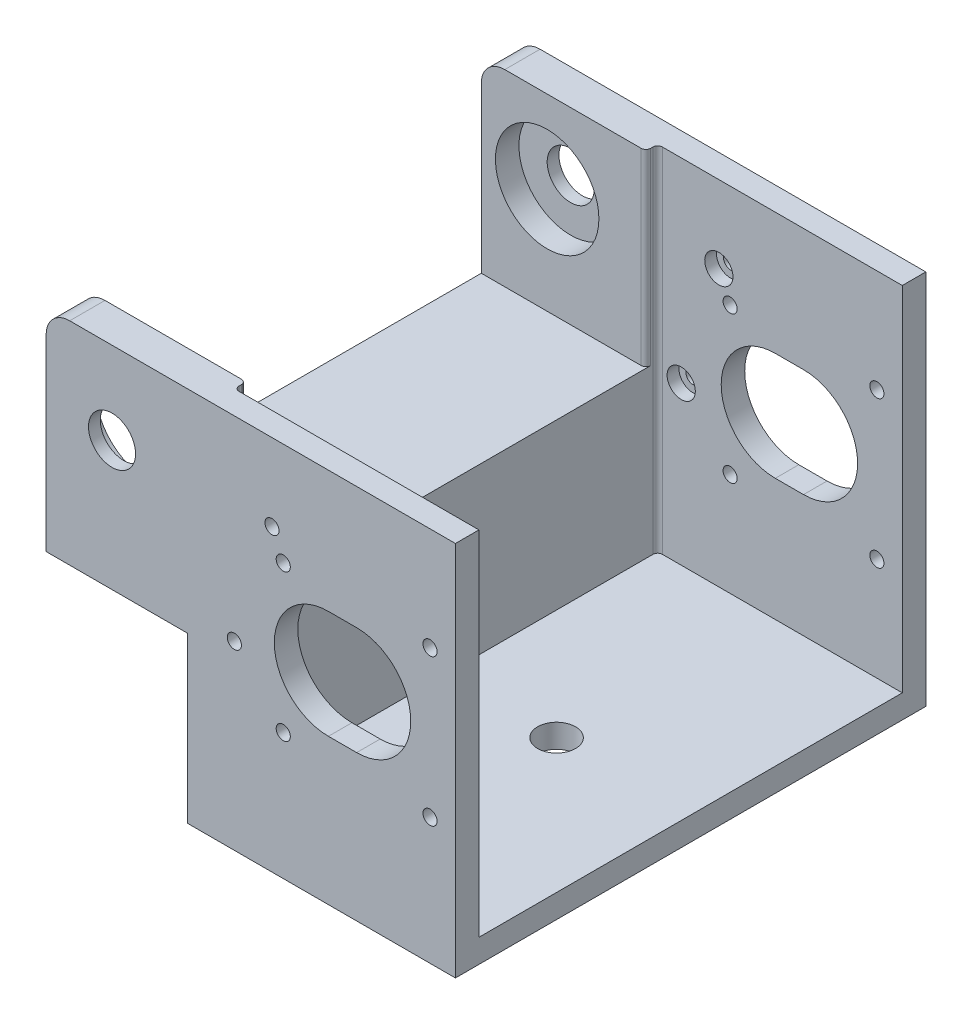
SolidWorks part; units mm, degrees
ref_plane "Front Plane" through (0, 0, 0) normal (0, 0, 1) x (1, 0, 0)
ref_plane "Top Plane" through (0, 0, 0) normal (0, 1, 0) x (1, 0, 0)
ref_plane "Right Plane" through (0, 0, 0) normal (1, 0, 0) x (0, 0, -1)
sketch "Sketch1" plane through (0, 0, 0) normal (0, 1, 0) x (1, 0, 0)
  line L1 (-28.5, 50) -> (28.5, 50)
  line L2 (-28.5, 50) -> (-28.5, -50)
  line L3 (-28.5, -50) -> (28.5, -50)
  line L4 (28.5, 50) -> (28.5, -50)
  line L5 (-28.5, 50) -> (28.5, -50) construction
  line L6 (-28.5, -50) -> (28.5, 50) construction
  point P0 (0, 0)
  dimension "D1" = 100
  dimension "D2" = 57
extrude "Boss-Extrude1" add sketch "Sketch1" along normal blind 80
sketch "Sketch3" plane through (28.5, 40, 0) normal (-1, 0, 0) x (0, 1, 0)
  line L1 (40, 45) -> (-35, 45)
  line L2 (40, 45) -> (40, -45)
  line L3 (40, -45) -> (-35, -45)
  line L4 (-35, 45) -> (-35, -45)
  line L5 (40, 45) -> (-35, -45) construction
  line L6 (40, -45) -> (-35, 45) construction
  line L10 (40, -50) -> (40, 50) construction
  line L11 (-40, -50) -> (-40, 50) construction
  line L12 (40, 50) -> (-40, 50) construction
  line L13 (40, -50) -> (-40, -50) construction
  point P0 (2.5, 0)
  dimension "D1" = 5
  dimension "D2" = 5
  dimension "D3" = 5
extrude "Cut-Extrude1" cut sketch "Sketch3" along normal blind 52
sketch "Sketch4" plane through (-40, 5, 0) normal (0, -1, 0) x (-1, 0, 0)
  line L0 (-40, 0) -> (-40, 10) construction
  circle A0 centre (-40, 0) radius 4.025
  circle A1 centre (-40, 10) radius 1.5 construction
  circle A2 centre (-30, 0) radius 1.5 construction
  circle A3 centre (-40, -10) radius 1.5 construction
  circle A4 centre (-50, 0) radius 1.5 construction
  dimension "D1" = 8.05
  dimension "D2" = 3
  dimension "D3" = 10
  dimension "D4" = 4
extrude "Cut-Extrude2" cut sketch "Sketch4" along normal through all
sketch "Sketch7" plane through (-28.5, 0, 0) normal (-1, 0, 0) x (0, 0, 1)
  line L0 (50, 80) -> (50, 0) construction
  line L1 (-50, 80) -> (-42.5, 80)
  line L2 (-50, 80) -> (-50, 35)
  line L4 (-42.5, 80) -> (-42.5, 40)
  line L5 (50, 80) -> (42.5, 80)
  line L6 (50, 80) -> (50, 35)
  line L8 (42.5, 80) -> (42.5, 40)
  line L9 (-50, 80) -> (50, 80) construction
  line L11 (-42.5, 40) -> (42.5, 40)
  line L13 (-50, 35) -> (50, 35)
  dimension "D1" = 7.5
  dimension "D2" = 40
  dimension "D3" = 5
extrude "Boss-Extrude2" add sketch "Sketch7" along normal blind 30
sketch "Sketch8" plane through (-28.5, 0, 0) normal (-1, 0, 0) x (0, 0, 1)
  line L4 (-42.5, 80) -> (-42.5, 40)
  line L5 (-42.5, 40) -> (42.5, 40)
  line L6 (42.5, 40) -> (42.5, 80)
  line L7 (42.5, 80) -> (-42.5, 80)
  line L8 (-42.5, 80) -> (-42.5, 40)
  line L9 (-42.5, 40) -> (42.5, 40)
  line L10 (42.5, 40) -> (42.5, 80)
  line L11 (42.5, 80) -> (-42.5, 80)
  dimension "D1" = 0
extrude "Cut-Extrude5" cut sketch "Sketch8" against normal up to next
sketch "Sketch5" plane through (0, 0, -50) normal (0, 0, -1) x (-1, 0, 0)
  line L0 (-4.5, 42.5) -> (30.0759, 42.5) construction
  line L1 (-4.5, 42.5) -> (-4.5, 17.143) construction
  line L2 (-28.5, 80) -> (58.5, 80) construction
  line L3 (-28.5, 80) -> (58.5, 80) construction
  line L4 (58.5, 80) -> (58.5, 35) construction
  line L5 (-23.1, 58.1) -> (-17.1, 58.1) construction
  line L6 (-23.1, 59.6) -> (-17.1, 59.6) construction
  line L7 (-23.1, 56.6) -> (-17.1, 56.6) construction
  line L8 (-28.5, 80) -> (-28.5, 0) construction
  line L9 (-1.5, 42.5) -> (-7.5, 42.5) construction
  line L10 (-1.5, 31) -> (-7.5, 31)
  line L11 (-1.5, 54) -> (-7.5, 54)
  line L12 (-23.1, 26.9) -> (-17.1, 26.9) construction
  line L13 (-23.1, 25.4) -> (-17.1, 25.4) construction
  line L14 (-23.1, 28.4) -> (-17.1, 28.4) construction
  line L15 (14.1, 26.9) -> (8.1, 26.9) construction
  line L16 (14.1, 25.4) -> (8.1, 25.4) construction
  line L17 (14.1, 28.4) -> (8.1, 28.4) construction
  line L18 (14.1, 58.1) -> (8.1, 58.1) construction
  line L19 (14.1, 59.6) -> (8.1, 59.6) construction
  line L20 (14.1, 56.6) -> (8.1, 56.6) construction
  line L21 (28.5, 35) -> (28.5, 0) construction
  circle A5 centre (44.5, 62.5) radius 5
  arc A7 (-23.1, 59.6) -> (-23.1, 56.6) centre (-23.1, 58.1) ccw construction
  arc A8 (-17.1, 56.6) -> (-17.1, 59.6) centre (-17.1, 58.1) ccw construction
  arc A9 (-1.5, 31) -> (-1.5, 54) centre (-1.5, 42.5) ccw
  arc A10 (-7.5, 54) -> (-7.5, 31) centre (-7.5, 42.5) ccw
  arc A11 (-23.1, 25.4) -> (-23.1, 28.4) centre (-23.1, 26.9) cw construction
  arc A12 (-17.1, 28.4) -> (-17.1, 25.4) centre (-17.1, 26.9) cw construction
  arc A13 (14.1, 25.4) -> (14.1, 28.4) centre (14.1, 26.9) ccw construction
  arc A14 (8.1, 28.4) -> (8.1, 25.4) centre (8.1, 26.9) ccw construction
  arc A15 (14.1, 59.6) -> (14.1, 56.6) centre (14.1, 58.1) cw construction
  arc A16 (8.1, 56.6) -> (8.1, 59.6) centre (8.1, 58.1) cw construction
  circle A17 centre (-23.1, 58.1) radius 1.5
  circle A18 centre (8.1, 58.1) radius 1.5
  circle A19 centre (8.1, 26.9) radius 1.5
  circle A20 centre (-23.1, 26.9) radius 1.5
  circle A21 centre (10.5, 63.6) radius 1.5
  circle A22 centre (18.5, 38.5) radius 1.5
  point P2 (-20.1, 58.1)
  point P8 (-20.1, 42.5)
  point P13 (-4.5, 42.5)
  point P31 (-20.1, 26.9)
  point P38 (11.1, 26.9)
  point P45 (11.1, 58.1)
  dimension "D5" = 15.6
  dimension "D8" = 6
  dimension "D9" = 10
  dimension "D2" = 1.5
  dimension "D7" = 11.5
  dimension "D12" = 24
  dimension "D13" = 3
  dimension "D16" = 4
  dimension "D3" = 15.6
  dimension "D4" = 6
  dimension "D6" = 37.5
  dimension "D10" = 17.5
  dimension "D11" = 14
  dimension "D14" = 10
  dimension "D15" = 4
  dimension "D17" = 8
extrude "Cut-Extrude3" cut sketch "Sketch5" against normal through all
sketch "Sketch9" plane through (0, 0, 0) normal (0, 0, 1) x (1, 0, 0)
  circle A0 centre (-44.5, 62.5) radius 11
  circle A1 centre (-10.5, 63.6) radius 3
  circle A2 centre (-18.5, 38.5) radius 3
  dimension "D1" = 22
  dimension "D2" = 6
extrude "Cut-Extrude6" cut sketch "Sketch9" against normal mid plane 95
fillet "Fillet1" radius 1 4 edges at (-23.5, 42.5, 45) (-23.5, 60, 42.5) (-23.5, 42.5, -45) (-23.5, 60, -42.5)
fillet "Fillet2" radius 5 2 edges at (-58.5, 80, 46.25) (-58.5, 80, -46.25)
